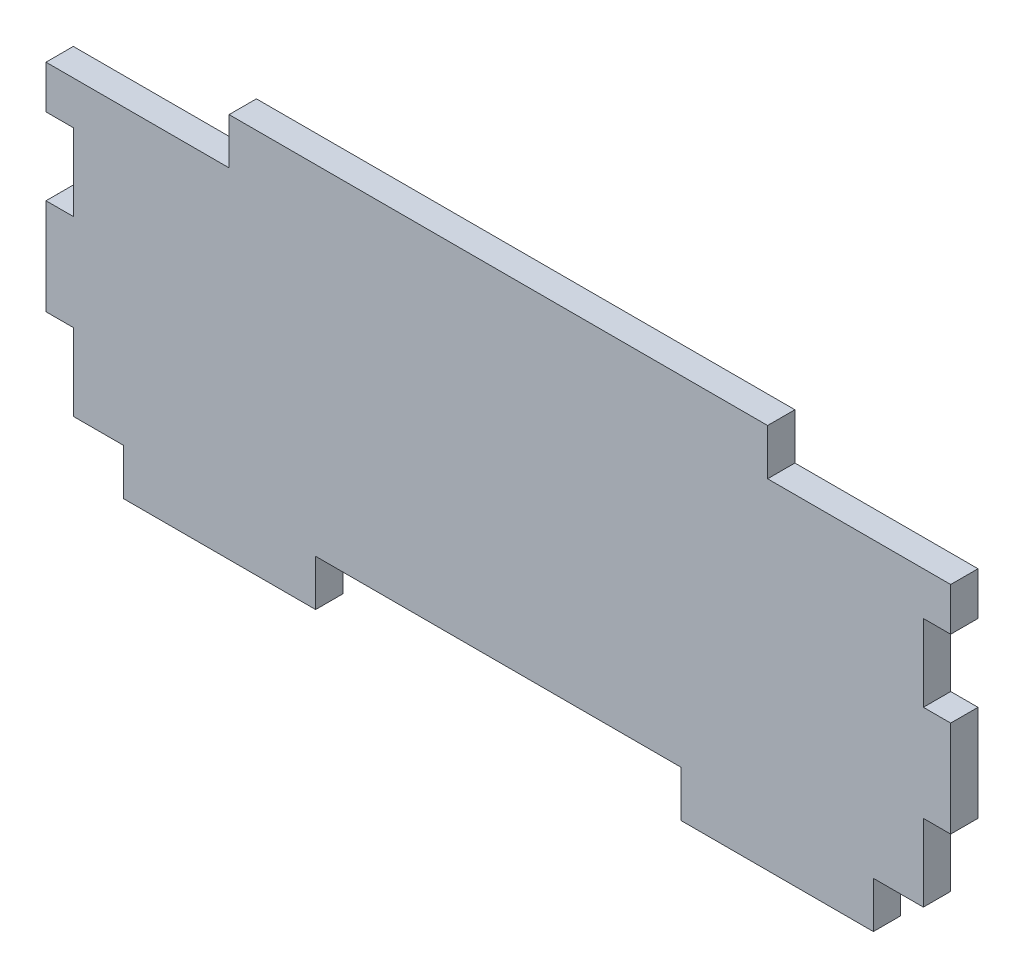
SolidWorks part; units mm, degrees
ref_plane "Front Plane" through (0, 0, 0) normal (0, 0, 1) x (1, 0, 0)
ref_plane "Top Plane" through (0, 0, 0) normal (0, 1, 0) x (1, 0, 0)
ref_plane "Right Plane" through (0, 0, 0) normal (1, 0, 0) x (0, 0, -1)
sketch "Sketch1" plane through (0, 0, 0) normal (0, 0, 1) x (1, 0, 0)
  line L0 (1.8034, 9.8044) -> (0, 9.8044) construction
  line L1 (1.8034, 16.1544) -> (1.8034, 9.8044) construction
  line L2 (1.8034, 16.1544) -> (0, 16.1544) construction
  line L3 (0, 21.2344) -> (0, 16.1544) construction
  line L4 (1.8034, 21.2344) -> (0, 21.2344) construction
  line L5 (1.8034, 24.0792) -> (1.8034, 21.2344) construction
  line L7 (1.8034, 9.8044) -> (0, 9.8044)
  line L8 (1.8034, 16.1544) -> (1.8034, 9.8044)
  line L9 (1.8034, 16.1544) -> (0, 16.1544)
  line L10 (0, 21.2344) -> (0, 16.1544)
  line L11 (1.8034, 21.2344) -> (0, 21.2344)
  line L12 (1.8034, 24.0792) -> (1.8034, 21.2344)
  line L13 (0, 9.8044) -> (0, 4.7244)
  line L14 (1.8034, 24.0792) -> (-10.287, 24.0792)
  line L15 (-10.287, 24.0792) -> (-10.287, 27.1272)
  line L16 (-10.287, 27.1272) -> (-45.847, 27.1272)
  line L17 (-45.847, 27.1272) -> (-45.847, 24.0792)
  line L18 (-45.847, 24.0792) -> (-57.9374, 24.0792)
  line L19 (-28.067, 27.1272) -> (-28.067, 4.7244) construction
  line L20 (-56.134, 9.8044) -> (-56.134, 4.7244)
  line L21 (-57.9374, 24.0792) -> (-57.9374, 21.2344)
  line L22 (-57.9374, 21.2344) -> (-56.134, 21.2344)
  line L23 (-56.134, 21.2344) -> (-56.134, 16.1544)
  line L24 (-57.9374, 16.1544) -> (-56.134, 16.1544)
  line L25 (-57.9374, 16.1544) -> (-57.9374, 9.8044)
  line L26 (-57.9374, 9.8044) -> (-56.134, 9.8044)
  line L27 (0, 4.7244) -> (-3.302, 4.7244)
  line L28 (-3.302, 4.7244) -> (-3.302, 1.6764)
  line L29 (-3.302, 1.6764) -> (-16.002, 1.6764)
  line L30 (-16.002, 1.6764) -> (-16.002, 4.7244)
  line L31 (-16.002, 4.7244) -> (-40.132, 4.7244)
  line L32 (-40.132, 4.7244) -> (-40.132, 1.6764)
  line L33 (-40.132, 1.6764) -> (-52.832, 1.6764)
  line L34 (-52.832, 1.6764) -> (-52.832, 4.7244)
  line L35 (-52.832, 4.7244) -> (-56.134, 4.7244)
  dimension "D1" = 56.134
  dimension "D2" = 35.56
  dimension "D3" = 3.048
  dimension "D4" = 16.002
  dimension "D5" = 16.002
  dimension "D6" = 3.048
  dimension "D7" = 12.7
extrude "Boss-Extrude1" add sketch "Sketch1" along normal blind 1.8034
